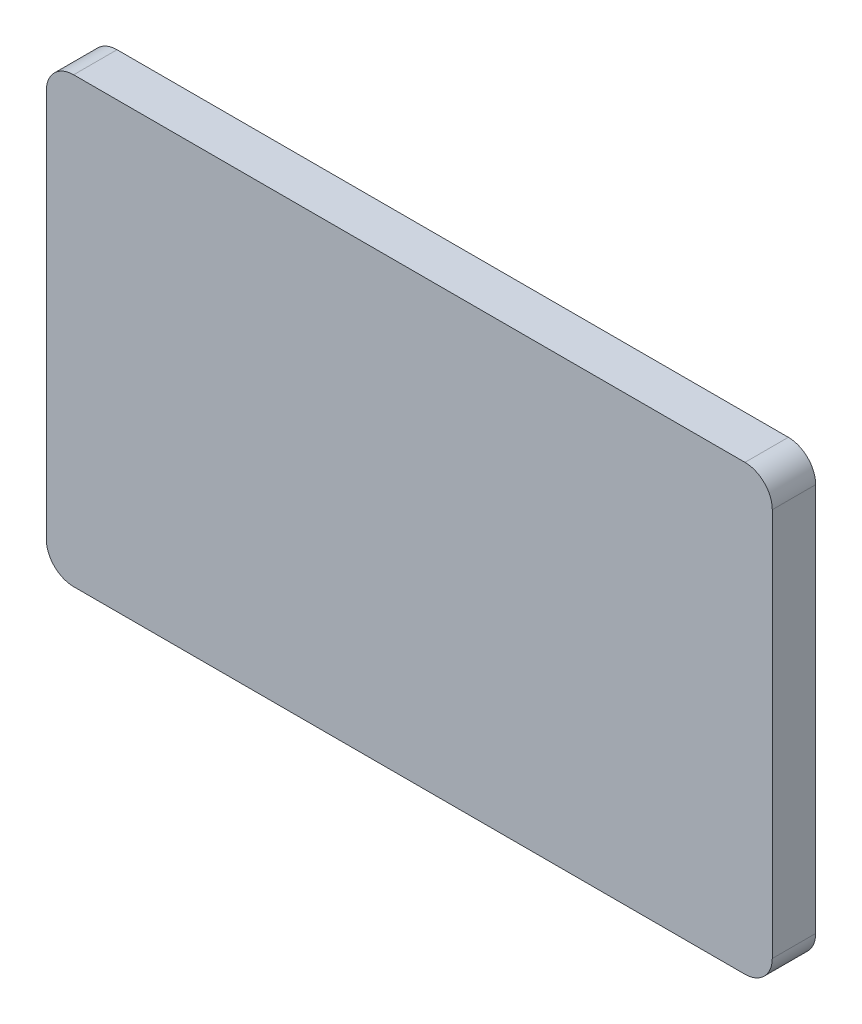
SolidWorks part; units mm, degrees
material "Acrylic (Medium-high impact)"
ref_plane "Front Plane" through (0, 0, 0) normal (0, 0, 1) x (1, 0, 0)
ref_plane "Top Plane" through (0, 0, 0) normal (0, 1, 0) x (1, 0, 0)
ref_plane "Right Plane" through (0, 0, 0) normal (1, 0, 0) x (0, 0, -1)
sketch "Sketch1" plane through (0, 0, 6.135) normal (0, 0, 1) x (1, 0, 0)
  line L0 (-3.5653, 51.6769) -> (-28.1253, 51.6769)
  line L1 (-29.1253, 50.6769) -> (-29.1253, 36.4569)
  line L2 (-28.1253, 35.4569) -> (-3.5653, 35.4569)
  line L3 (-2.5653, 36.4569) -> (-2.5653, 50.6769)
  line L4 (-5.0653, 37.9569) -> (-5.0653, 49.1769)
  line L5 (-5.0653, 49.1769) -> (-26.6253, 49.1769)
  line L6 (-26.6253, 49.1769) -> (-26.6253, 37.9569)
  line L7 (-26.6253, 37.9569) -> (-5.0653, 37.9569)
  line L8 (-5.0653, 37.9569) -> (-5.0653, 49.1769) construction
  line L9 (-5.0653, 49.1769) -> (-26.6253, 49.1769) construction
  line L10 (-26.6253, 49.1769) -> (-26.6253, 37.9569) construction
  line L11 (-26.6253, 37.9569) -> (-5.0653, 37.9569) construction
  line L12 (-2.5653, 51.6769) -> (-29.1253, 51.6769) construction
  line L13 (-29.1253, 51.6769) -> (-29.1253, 35.4569) construction
  line L14 (-29.1253, 35.4569) -> (-2.5653, 35.4569) construction
  line L15 (-2.5653, 35.4569) -> (-2.5653, 51.6769) construction
  arc A0 (-28.1253, 51.6769) -> (-29.1253, 50.6769) centre (-28.1253, 50.6769) ccw
  arc A1 (-29.1253, 36.4569) -> (-28.1253, 35.4569) centre (-28.1253, 36.4569) ccw
  arc A2 (-3.5653, 35.4569) -> (-2.5653, 36.4569) centre (-3.5653, 36.4569) ccw
  arc A3 (-3.5653, 51.6769) -> (-2.5653, 50.6769) centre (-3.5653, 50.6769) cw
  dimension "D3" = 1
  dimension "D1" = 0
  dimension "D2" = 2.5
extrude "Boss-Extrude1" add sketch "Sketch1" along normal blind 1.5875 from offset 0.5
equation "\"D1@Boss-Extrude1\"=25.4/16"
